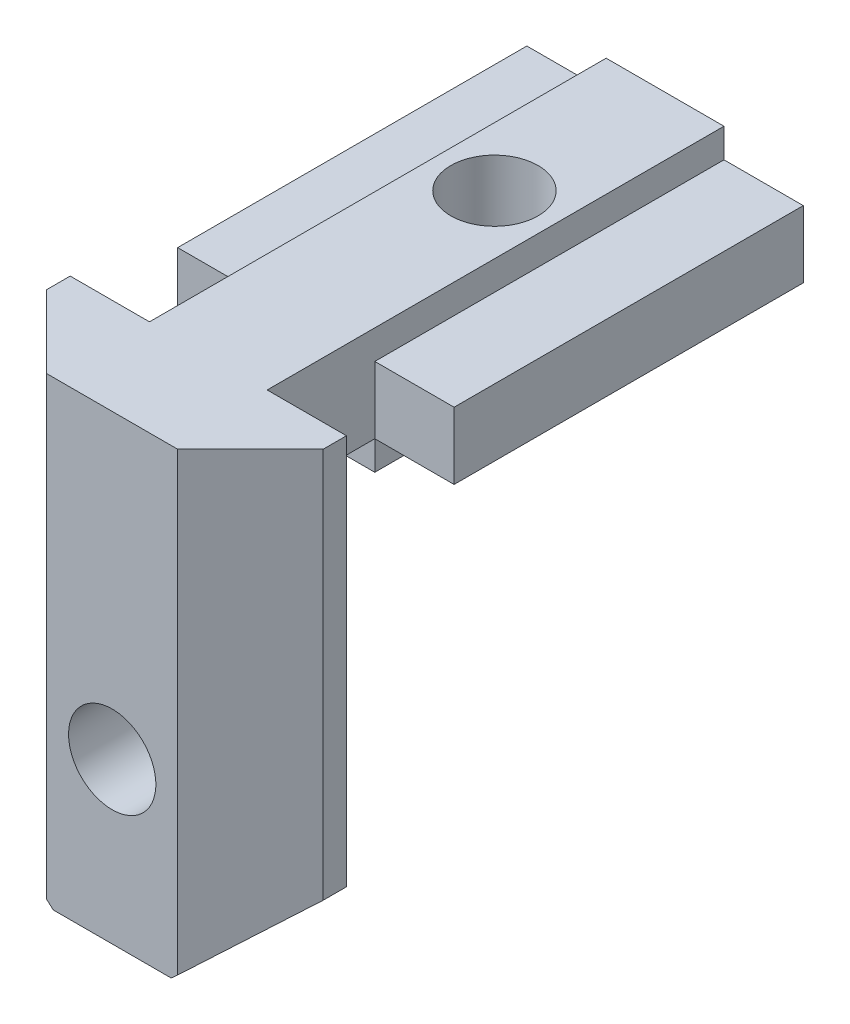
SolidWorks part; units mm, degrees
ref_plane "前视基准面" through (0, 0, 0) normal (0, 0, 1) x (1, 0, 0)
ref_plane "上视基准面" through (0, 0, 0) normal (0, 1, 0) x (1, 0, 0)
ref_plane "右视基准面" through (0, 0, 0) normal (1, 0, 0) x (0, 0, -1)
sketch "草图2" plane through (0, 0, 0) normal (0, 0, 1) x (1, 0, 0)
  line L1 (-9.5, -15.85) -> (9.5, -15.85)
  line L2 (-9.5, -15.85) -> (-9.5, 15.85)
  line L3 (-9.5, 15.85) -> (9.5, 15.85)
  line L4 (9.5, -15.85) -> (9.5, 15.85)
  line L5 (-9.5, -15.85) -> (9.5, 15.85) construction
  line L6 (-9.5, 15.85) -> (9.5, -15.85) construction
  point P0 (0, 0)
  dimension "D1" = 19
  dimension "D2" = 31.7
extrude "凸台-拉伸1" add sketch "草图2" along normal blind 6.6
sketch "草图3" plane through (0, 15.85, 0) normal (0, 1, 0) x (1, 0, 0)
  line L0 (-9.5, -6.6) -> (9.5, -6.6)
  line L1 (-9.5, -6.6) -> (-9.5, 31.4)
  line L2 (9.5, -6.6) -> (9.5, 31.4)
  line L3 (-9.5, 31.4) -> (9.5, 31.4)
  dimension "D1" = 38
extrude "凸台-拉伸2" add sketch "草图3" against normal blind 6.6
sketch "草图4" plane through (0, 0, 0) normal (0, 0, -1) x (-1, 0, 0)
  line L0 (-4.05, -15.85) -> (4.05, -15.85)
  line L1 (-4.05, -15.85) -> (-4.05, 9.2543)
  line L2 (4.05, -15.85) -> (4.05, 9.2543)
  line L3 (-4.05, 9.2543) -> (4.05, 9.2543)
  line L4 (9.5, -15.85) -> (-9.5, -15.85) construction
  point P6 (0, -15.85)
  point P7 (0, -15.85)
  dimension "D1" = 8.1
extrude "凸台-拉伸3" add sketch "草图4" along normal blind 2
sketch "草图5" plane through (0, 9.25, 0) normal (0, -1, 0) x (1, 0, 0)
  line L0 (-4.05, -31.4) -> (4.05, -31.4)
  line L1 (-4.05, -31.4) -> (-4.05, -7.4)
  line L2 (4.05, -31.4) -> (4.05, -7.4)
  line L3 (-4.05, -7.4) -> (4.05, -7.4)
  line L4 (9.5, -31.4) -> (-9.5, -31.4) construction
  point P6 (0, -31.4)
  point P7 (0, -31.4)
  dimension "D1" = 8.1
  dimension "D2" = 24
extrude "凸台-拉伸4" add sketch "草图5" along normal blind 2
sketch "草图6" plane through (0, 9.25, 0) normal (0, -1, 0) x (1, 0, 0)
  line L0 (-4.05, -7.4) -> (-9.5, -7.4)
  line L1 (-4.05, -7.4) -> (-4.05, -0.014)
  line L2 (-9.5, -7.4) -> (-9.5, -0.014)
  line L3 (-4.05, -0.014) -> (-9.5, -0.014)
  line L4 (-9.5, -31.4) -> (-9.5, 0) construction
  line L6 (4.05, -7.4) -> (9.5, -7.4)
  line L7 (4.05, -7.4) -> (4.05, -0.0021)
  line L8 (9.5, -7.4) -> (9.5, -0.0021)
  line L9 (4.05, -0.0021) -> (9.5, -0.0021)
  line L10 (9.5, 0) -> (9.5, -31.4) construction
extrude "切除-拉伸1" cut sketch "草图6" against normal through all
chamfer "倒角1" distance 5 angle 45 2 edges at (-9.5, 0, 6.6) (9.5, 0, 6.6)
sketch "草图7" plane through (0, 0, -2) normal (0, 0, -1) x (-1, 0, 0)
  circle A0 centre (0, -4.8597) radius 3
  dimension "D1" = 6
extrude "切除-拉伸2" cut sketch "草图7" against normal through all
sketch "草图8" plane through (0, 7.25, 0) normal (0, -1, 0) x (1, 0, 0)
  circle A0 centre (0, -19.674) radius 3
  dimension "D1" = 6
extrude "切除-拉伸3" cut sketch "草图8" against normal through all
sketch "草图9" plane through (0, 0, -31.4) normal (0, 0, -1) x (-1, 0, 0)
  line L1 (-9.5, 15.85) -> (-4.05, 15.85)
  line L2 (-9.5, 15.85) -> (-9.5, 13.85)
  line L3 (-9.5, 13.85) -> (-4.05, 13.85)
  line L4 (-4.05, 15.85) -> (-4.05, 13.85)
  line L5 (9.5, 15.85) -> (4.05, 15.85)
  line L6 (9.5, 15.85) -> (9.5, 13.85)
  line L7 (9.5, 13.85) -> (4.05, 13.85)
  line L8 (4.05, 15.85) -> (4.05, 13.85)
  line L9 (4.05, 7.25) -> (4.05, 9.25) construction
  line L10 (-4.05, 7.25) -> (-4.05, 9.25) construction
  dimension "D1" = 2
  dimension "D2" = 2
extrude "切除-拉伸4" cut sketch "草图9" against normal blind 25
sketch "草图10" plane through (0, 0, -2) normal (0, 0, -1) x (-1, 0, 0)
  line L0 (-4.05, -15.85) -> (-9.5, -10.9993)
  line L1 (-9.5, -15.85) -> (-9.5, 9.25) construction
  line L2 (-9.5, -10.9993) -> (-9.5, -15.85)
  line L3 (-9.5, -15.85) -> (-4.05, -15.85)
extrude "切除-拉伸5" cut sketch "草图10" against normal through all
mirror "镜向1" about plane through (0, 0, 0) normal (1, 0, 0) of "切除-拉伸5"
